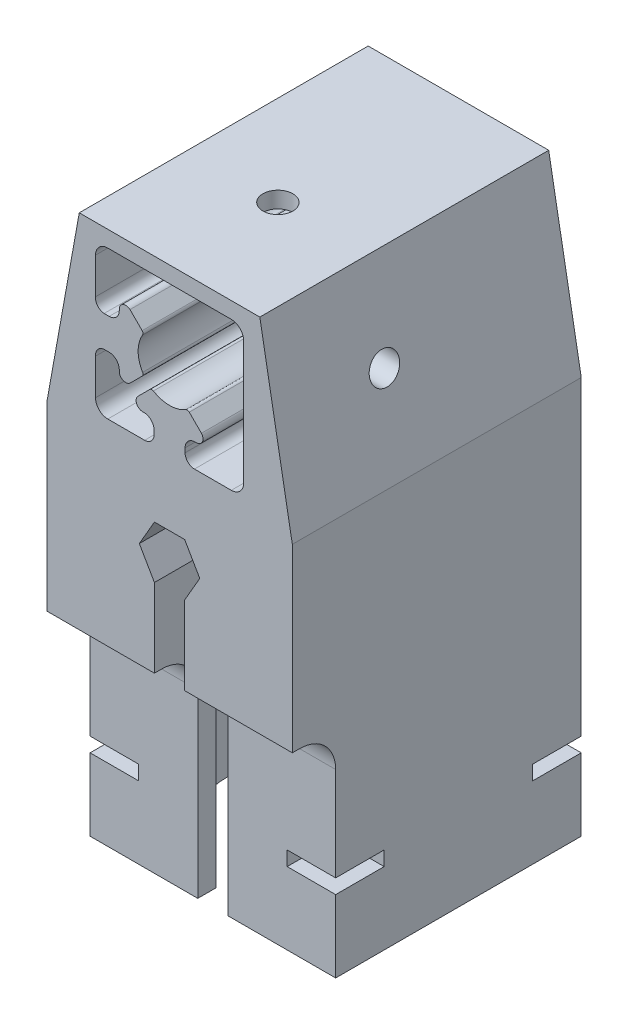
SolidWorks part; units mm, degrees
ref_plane "Front Plane" through (0, 0, 0) normal (0, 0, 1) x (1, 0, 0)
ref_plane "Top Plane" through (0, 0, 0) normal (0, 1, 0) x (1, 0, 0)
ref_plane "Right Plane" through (0, 0, 0) normal (1, 0, 0) x (0, 0, -1)
sketch "Sketch1" plane through (0, 0, 0) normal (0, 0, 1) x (1, 0, 0)
  line L0 (25, 0) -> (-25, 0)
  line L1 (0, -315.3635) -> (0, 315.3635) construction
  line L2 (-34, -160) -> (34, -160)
  line L3 (-34, -50) -> (34, -50) construction
  line L4 (-25, 0) -> (-34, -50)
  line L5 (-34, -160) -> (-34, -50)
  line L6 (25, 0) -> (34, -50)
  line L7 (34, -50) -> (34, -160)
  point P4 (0, 0)
  point P8 (0, 0)
  point P11 (0, -160)
  point P14 (0, -50)
  dimension "D1" = 160
  dimension "D2" = 50
  dimension "D3" = 68
  dimension "D4" = 50
extrude "Boss-Extrude1" add sketch "Sketch1" along normal blind 80
sketch "Sketch2" plane through (0, -160, 0) normal (0, -1, 0) x (1, 0, 0)
  line L0 (34, 80) -> (34, 0) construction
  line L1 (-34, 80) -> (34, 80)
  line L2 (-34, 80) -> (-34, 68)
  line L3 (-34, 68) -> (34, 68)
  line L4 (34, 80) -> (34, 68)
  dimension "D1" = 12
extrude "Cut-Extrude1" cut sketch "Sketch2" against normal blind 60
fillet "Fillet1" radius 10 1 edges at (0, -100, 68)
sketch "Sketch5" plane through (0, 0, 80) normal (0, 0, 1) x (1, 0, 0)
  line L0 (17.1, -45.1) -> (6.9, -45.1)
  line L1 (-20.1, -4.9) -> (-20.1, -45.1) construction
  line L2 (-20.1, -45.1) -> (20.1, -45.1) construction
  line L3 (-20.1, -4.9) -> (20.1, -45.1) construction
  line L4 (-20.1, -45.1) -> (0, -25) construction
  line L5 (4.7, -42.9) -> (4.7, -41.72)
  line L6 (5.7399, -32.2955) -> (9.12, -35.6756)
  line L7 (7.1, -39.32) -> (7.4605, -39.32)
  line L8 (-20.1, -42.1) -> (-20.1, -32.1)
  line L9 (-18.1, -29.7) -> (-16.72, -29.7)
  line L10 (-17.1, -45.1) -> (-6.9, -45.1)
  line L11 (-4.7, -42.9) -> (-4.7, -41.72)
  line L12 (-5.7399, -32.2955) -> (-9.12, -35.6756)
  line L13 (-7.2955, -30.7399) -> (-10.6756, -34.12)
  line L14 (-7.1, -39.32) -> (-7.4605, -39.32)
  line L15 (-14.32, -32.1) -> (-14.32, -32.4605)
  line L16 (-20.1, -7.9) -> (-20.1, -17.9)
  line L17 (-18.1, -20.3) -> (-16.72, -20.3)
  line L18 (-7.2955, -19.2601) -> (-10.6756, -15.88)
  line L19 (-14.32, -17.9) -> (-14.32, -17.5395)
  line L20 (25, 0) -> (-25, 0)
  line L21 (25, 0) -> (25, -50)
  line L22 (25, -50) -> (-25, -50)
  line L23 (-25, 0) -> (-25, -50)
  line L24 (25, 0) -> (20.1, -4.9) construction
  line L25 (25, -50) -> (-25, 0) construction
  line L26 (-17.1, -4.9) -> (-7.1, -4.9)
  line L27 (0, -25) -> (-25, -50) construction
  line L28 (19.2213, -5.7787) -> (18.6948, -6.3052) construction
  line L29 (20.1, -42.1) -> (20.1, -31.9)
  line L30 (17.1, -4.9) -> (7.1, -4.9)
  line L31 (20.1, -7.9) -> (20.1, -18.1)
  line L32 (20.1, -31.9) -> (20.1, -18.1)
  line L33 (7.1, -4.9) -> (-7.1, -4.9)
  line L34 (17.1, -45.5) -> (6.9, -45.5)
  line L35 (4.3, -42.9) -> (4.3, -41.72)
  line L36 (7.1, -38.92) -> (7.4605, -38.92)
  line L37 (5.457, -32.5783) -> (8.8269, -35.9482)
  line L38 (-5.457, -32.5783) -> (-8.8269, -35.9482)
  line L39 (-7.1, -38.92) -> (-7.4605, -38.92)
  line L40 (-4.3, -42.9) -> (-4.3, -41.72)
  line L41 (-17.1, -45.5) -> (-6.9, -45.5)
  line L42 (-20.5, -42.1) -> (-20.5, -32.1182)
  line L43 (-18.1166, -29.3) -> (-16.72, -29.3)
  line L44 (-13.92, -32.1) -> (-13.92, -32.4605)
  line L45 (-7.5783, -30.457) -> (-10.9482, -33.8269)
  line L46 (-7.5783, -19.543) -> (-10.9482, -16.1731)
  line L47 (-13.92, -17.9) -> (-13.92, -17.5395)
  line L48 (-18.1166, -20.7) -> (-16.72, -20.7)
  line L49 (-20.5, -7.9) -> (-20.5, -17.8818)
  line L50 (-17.1, -4.5) -> (-7.1, -4.5)
  line L51 (7.1, -4.5) -> (-7.1, -4.5)
  line L52 (17.1, -4.5) -> (7.1, -4.5)
  line L53 (20.5, -7.9) -> (20.5, -18.1)
  line L54 (20.5, -31.9) -> (20.5, -18.1)
  line L55 (20.5, -42.1) -> (20.5, -31.9)
  line L58 (25, -50) -> (-25, 0) construction
  line L59 (25, 0) -> (-25, 0) construction
  line L60 (25, 0) -> (25, -50) construction
  line L61 (25, -50) -> (-25, -50) construction
  line L62 (-25, 0) -> (-25, -50) construction
  line L63 (-25, -50) -> (25, 0) construction
  arc A0 (17.1, -45.1) -> (20.1, -42.1) centre (17.1, -42.1) ccw
  arc A1 (7.4605, -39.32) -> (9.12, -35.6756) centre (7.4605, -37.12) ccw
  arc A2 (4.7, -41.72) -> (7.1, -39.32) centre (7.1, -41.72) cw
  arc A3 (6.9, -45.1) -> (4.7, -42.9) centre (6.9, -42.9) cw
  arc A4 (-20.1, -42.1) -> (-17.1, -45.1) centre (-17.1, -42.1) ccw
  arc A5 (-6.9, -45.1) -> (-4.7, -42.9) centre (-6.9, -42.9) ccw
  arc A6 (-4.7, -41.72) -> (-7.1, -39.32) centre (-7.1, -41.72) ccw
  arc A7 (-14.32, -32.4605) -> (-10.6756, -34.12) centre (-12.12, -32.4605) ccw
  arc A8 (-7.4605, -39.32) -> (-9.12, -35.6756) centre (-7.4605, -37.12) cw
  arc A9 (-16.72, -29.7) -> (-14.32, -32.1) centre (-16.72, -32.1) cw
  arc A10 (-20.1, -32.1) -> (-18.1, -29.7) centre (-17.9099, -31.8918) cw
  arc A11 (-17.1, -4.9) -> (-20.1, -7.9) centre (-17.1, -7.9) ccw
  arc A12 (-20.1, -17.9) -> (-18.1, -20.3) centre (-17.9099, -18.1082) ccw
  arc A13 (-16.72, -20.3) -> (-14.32, -17.9) centre (-16.72, -17.9) ccw
  arc A14 (-14.32, -17.5395) -> (-10.6756, -15.88) centre (-12.12, -17.5395) cw
  arc A15 (17.1, -4.9) -> (20.1, -7.9) centre (17.1, -7.9) cw
  arc A16 (-4.2735, -32.1153) -> (4.2735, -32.1153) centre (0, -25) ccw
  arc A17 (-7.1153, -20.7265) -> (-7.1153, -29.2735) centre (0, -25) ccw
  arc A18 (-5.7399, -32.2955) -> (-4.2735, -32.1153) centre (-4.8913, -33.144) cw
  arc A19 (-7.2955, -30.7399) -> (-7.1153, -29.2735) centre (-8.144, -29.8913) ccw
  arc A20 (-7.2955, -19.2601) -> (-7.1153, -20.7265) centre (-8.144, -20.1087) cw
  arc A21 (5.7399, -32.2955) -> (4.2735, -32.1153) centre (4.8913, -33.144) ccw
  arc A22 (6.9, -45.5) -> (4.3, -42.9) centre (6.9, -42.9) cw
  arc A23 (4.3, -41.72) -> (7.1, -38.92) centre (7.1, -41.72) cw
  arc A24 (7.4605, -38.92) -> (8.8269, -35.9482) centre (7.4605, -37.12) ccw
  arc A25 (5.457, -32.5783) -> (4.4794, -32.4582) centre (4.8913, -33.144) ccw
  arc A26 (-4.4794, -32.4582) -> (4.4794, -32.4582) centre (0, -25) ccw
  arc A27 (-5.457, -32.5783) -> (-4.4794, -32.4582) centre (-4.8913, -33.144) cw
  arc A28 (-7.4605, -38.92) -> (-8.8269, -35.9482) centre (-7.4605, -37.12) cw
  arc A29 (-4.3, -41.72) -> (-7.1, -38.92) centre (-7.1, -41.72) ccw
  arc A30 (-6.9, -45.5) -> (-4.3, -42.9) centre (-6.9, -42.9) ccw
  arc A31 (-20.5, -42.1) -> (-17.1, -45.5) centre (-17.1, -42.1) ccw
  arc A32 (-20.5, -32.1182) -> (-18.1166, -29.3) centre (-17.9099, -31.8918) cw
  arc A33 (-16.72, -29.3) -> (-13.92, -32.1) centre (-16.72, -32.1) cw
  arc A34 (-13.92, -32.4605) -> (-10.9482, -33.8269) centre (-12.12, -32.4605) ccw
  arc A35 (-7.5783, -30.457) -> (-7.4582, -29.4794) centre (-8.144, -29.8913) ccw
  arc A36 (-7.4582, -20.5206) -> (-7.4582, -29.4794) centre (0, -25) ccw
  arc A37 (-7.5783, -19.543) -> (-7.4582, -20.5206) centre (-8.144, -20.1087) cw
  arc A38 (-13.92, -17.5395) -> (-10.9482, -16.1731) centre (-12.12, -17.5395) cw
  arc A39 (-16.72, -20.7) -> (-13.92, -17.9) centre (-16.72, -17.9) ccw
  arc A40 (-20.5, -17.8818) -> (-18.1166, -20.7) centre (-17.9099, -18.1082) ccw
  arc A41 (-17.1, -4.5) -> (-20.5, -7.9) centre (-17.1, -7.9) ccw
  arc A42 (17.1, -4.5) -> (20.5, -7.9) centre (17.1, -7.9) cw
  arc A43 (17.1, -45.5) -> (20.5, -42.1) centre (17.1, -42.1) ccw
  point P0 (0, -25)
  point P146 (0, 0)
  point P147 (0, -25)
  dimension "D1" = 3
  dimension "D2" = 1.2
  dimension "D3" = 1.2
  dimension "D4" = 2.2
  dimension "D5" = 2.4
  dimension "D6" = 2.2
  dimension "D7" = 1.1
  dimension "D8" = 1.1
  dimension "D9" = 50
  dimension "D10" = 0
extrude "Cut-Extrude6" cut sketch "Sketch5" against normal blind 60 contours L34 A22 L35 A23 L36 A24 L37 A25 A26 A27 L38 A28 L39 A29 L40 A30 L41 A31 L42 A32 L43 A33 L44 A34 L45 A35 A36 A37 L46 A38 L47 A39 L48 A40 L49 A41 L50 L51 L52 A42 L53 L54 L55 A43
sketch "Sketch6" plane through (0, -160, 0) normal (0, -1, 0) x (1, 0, 0)
  line L0 (-34, 68) -> (34, 0) construction
  line L1 (-34, 68) -> (34, 68) construction
  line L2 (-34, 68) -> (-34, 0) construction
  line L3 (-34, 0) -> (34, 0) construction
  line L4 (34, 68) -> (34, 0) construction
  line L5 (34, 68) -> (-34, 0) construction
  circle A0 centre (0, 34) radius 29.25
  point P8 (0, 0)
  point P9 (0, 34)
extrude "Cut-Extrude7" cut sketch "Sketch6" against normal blind 95
sketch "Sketch7" plane through (0, -160, 0) normal (0, -1, 0) x (1, 0, 0)
  line L0 (-34, 68) -> (34, 0) construction
  line L1 (34, 68) -> (-34, 0) construction
  circle A0 centre (0, 34) radius 33.25 construction
  circle A1 centre (-23.5113, 57.5113) radius 3
  circle A2 centre (23.5113, 57.5113) radius 3
  circle A3 centre (23.5113, 10.4887) radius 3
  circle A4 centre (-23.5113, 10.4887) radius 3
  point P11 (-23.5113, 57.5113)
  point P12 (0, 34)
  point P13 (23.5113, 57.5113)
  point P14 (23.5113, 10.4887)
  point P15 (-23.5113, 10.4887)
  dimension "D1" = 6
  dimension "D2" = 66.5
extrude "Cut-Extrude8" cut sketch "Sketch7" against normal blind 41
sketch "Sketch8" plane through (0, -160, 0) normal (0, -1, 0) x (1, 0, 0)
  line L15 (-26.4507, 54.5719) -> (-22.4354, 53.496)
  line L16 (-22.4354, 53.496) -> (-19.496, 56.4354)
  line L17 (-19.496, 56.4354) -> (-20.5719, 60.4507)
  line L24 (-26.4507, 54.5719) -> (-34, 54.5719)
  line L25 (20.5719, 60.4507) -> (19.496, 56.4354)
  line L26 (-34, 68) -> (-34, 0) construction
  line L27 (-34, 68) -> (34, 0) construction
  line L28 (-20.5719, 60.4507) -> (-20.5719, 68)
  line L29 (-34, 68) -> (34, 68) construction
  line L30 (-20.5719, 68) -> (-34, 68)
  line L31 (-34, 68) -> (-34, 54.5719)
  line L32 (19.496, 56.4354) -> (22.4354, 53.496)
  line L37 (22.4354, 53.496) -> (26.4507, 54.5719)
  line L38 (20.5719, 60.4507) -> (20.5719, 68)
  line L39 (26.4507, 54.5719) -> (34, 54.5719)
  line L40 (34, 54.5719) -> (34, 68)
  line L43 (34, 68) -> (20.5719, 68)
  line L44 (26.4507, 13.4281) -> (22.4354, 14.504)
  line L45 (22.4354, 14.504) -> (19.496, 11.5646)
  line L46 (19.496, 11.5646) -> (20.5719, 7.5493)
  line L47 (26.4507, 13.4281) -> (34, 13.4281)
  line L48 (20.5719, 7.5493) -> (20.5719, 0)
  line L49 (20.5719, 0) -> (34, 0)
  line L50 (34, 0) -> (34, 13.4281)
  line L51 (-20.5719, 7.5493) -> (-19.496, 11.5646)
  line L52 (-19.496, 11.5646) -> (-22.4354, 14.504)
  line L53 (-22.4354, 14.504) -> (-26.4507, 13.4281)
  line L54 (-20.5719, 7.5493) -> (-20.5719, 0)
  line L55 (-26.4507, 13.4281) -> (-34, 13.4281)
  line L56 (-34, 13.4281) -> (-34, 0)
  line L57 (-34, 0) -> (-20.5719, 0)
  circle A0 centre (23.5113, 57.5113) radius 3.6 construction
  circle A1 centre (23.5113, 10.4887) radius 3.6 construction
  circle A2 centre (-23.5113, 57.5113) radius 3.6 construction
  circle A3 centre (-23.5113, 10.4887) radius 3.6 construction
  point P36 (0, 34)
  dimension "D1" = 8.3138
extrude "Cut-Extrude9" cut sketch "Sketch8" against normal blind 4 from offset 20 offset against normal yes
sketch "Sketch9" plane through (0, 0, 80) normal (0, 0, 1) x (1, 0, 0)
  line L0 (-34, -160) -> (34, -160) construction
  line L1 (4.1858, -63.75) -> (-4.1858, -63.75)
  line L2 (-4.1858, -63.75) -> (-8.3716, -71)
  line L3 (-8.3716, -71) -> (-4.1858, -78.25)
  line L4 (-4.1858, -78.25) -> (4.1858, -78.25)
  line L5 (4.1858, -78.25) -> (8.3716, -71)
  line L6 (8.3716, -71) -> (4.1858, -63.75)
  circle A0 centre (0, -71) radius 7.25 construction
  dimension "D1" = 14.5
  dimension "D2" = 89
extrude "Cut-Extrude10" cut sketch "Sketch9" against normal blind 30
sketch "Sketch10" plane through (0, -78.25, 0) normal (0, 1, 0) x (1, 0, 0)
  line L3 (-4.1858, -62.9489) -> (-4.1858, -80)
  line L4 (-4.1858, -80) -> (4.1858, -80)
  line L5 (4.1858, -80) -> (4.1858, -62.9489)
  line L6 (-4.1858, -62.9489) -> (-4.1858, -80)
  line L7 (-4.1858, -80) -> (4.1858, -80)
  line L8 (4.1858, -80) -> (4.1858, -62.9489)
  arc A1 (-4.1858, -62.9489) -> (4.1858, -62.9489) centre (0, -34) ccw
  arc A2 (-4.1858, -62.9489) -> (4.1858, -62.9489) centre (0, -34) ccw
  dimension "D1" = 0
extrude "Cut-Extrude11" cut sketch "Sketch10" against normal blind 90
sketch "Sketch11" plane through (0, 0, 0) normal (0, 1, 0) x (1, 0, 0)
  line L0 (0, 0) -> (0, -80) construction
  line L1 (25, -80) -> (-25, -80) construction
  circle A0 centre (0, -50) radius 4.15
  point P7 (0, -32.7986)
  point P8 (0, -28.2637)
  dimension "D1" = 30
extrude "Cut-Extrude12" cut sketch "Sketch11" against normal blind 18 contours A0
sketch "Sketch12" plane through (20.5, 0, 0) normal (-1, 0, 0) x (0, 0, 1)
  line L0 (20, -7.9) -> (80, -42.1) construction
  line L1 (80, -7.9) -> (20, -42.1) construction
  circle A0 centre (50, -25) radius 4.15
  point P8 (50, -25)
  dimension "D1" = 8.3
extrude "Cut-Extrude13" cut sketch "Sketch12" against normal blind 18
